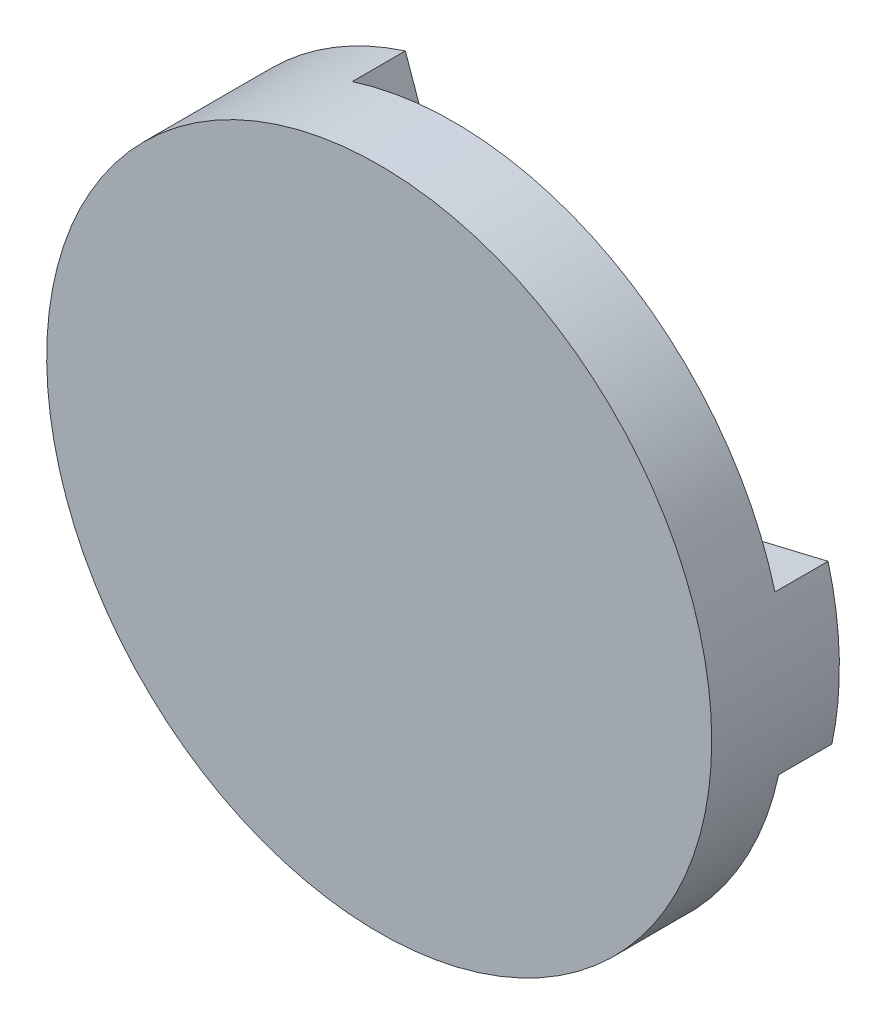
SolidWorks part; units mm, degrees
ref_plane "Front Plane" through (0, 0, 0) normal (0, 0, 1) x (1, 0, 0)
ref_plane "Top Plane" through (0, 0, 0) normal (0, 1, 0) x (1, 0, 0)
ref_plane "Right Plane" through (0, 0, 0) normal (1, 0, 0) x (0, 0, -1)
sketch "Sketch2" plane through (0, 0, 0) normal (0, 0, 1) x (1, 0, 0)
  line L0 (-57.2013, -53.6007) -> (-70.43, -69.0249) construction
  line L1 (-58.6979, -75.4263) -> (-52.8865, -55.955) construction
  line L2 (-37.8874, -46.8061) -> (-17.9153, -50.5504) construction
  line L3 (-18.2376, -37.1893) -> (-38.0059, -41.8922) construction
  line L4 (-53.4287, -33.477) -> (-60.1721, -14.3086) construction
  line L5 (-71.5819, -21.2682) -> (-57.625, -36.0366) construction
  line L6 (-57.2013, -53.6007) -> (-72.0836, -70.9529) construction
  line L7 (-59.4243, -77.8602) -> (-52.8865, -55.955) construction
  line L8 (-37.8874, -46.8061) -> (-15.4188, -51.0184) construction
  line L9 (-15.7666, -36.6015) -> (-38.0059, -41.8922) construction
  line L10 (-53.4287, -33.477) -> (-61.015, -11.9125) construction
  line L11 (-73.3265, -19.4221) -> (-57.625, -36.0366) construction
  line L26 (-39.1, -47.5962) -> (-14.634, -52.1829)
  line L27 (-15.0388, -35.4004) -> (-39.2552, -41.1615)
  line L28 (-52.1381, -34.1322) -> (-60.3989, -10.6506)
  line L29 (-74.7306, -19.3924) -> (-57.6331, -37.4839)
  line L30 (-58.7481, -79.091) -> (-51.629, -55.2384)
  line L31 (-57.2793, -52.1555) -> (-73.4845, -71.0503)
  arc A0 (-57.2013, -53.6007) -> (-52.8865, -55.955) centre (-49.5058, -44.6279) ccw construction
  arc A2 (-37.8874, -46.8061) -> (-38.0059, -41.8922) centre (-49.5058, -44.6279) ccw construction
  arc A4 (-53.4287, -33.477) -> (-57.625, -36.0366) centre (-49.5058, -44.6279) ccw construction
  arc A6 (-57.2013, -53.6007) -> (-52.8865, -55.955) centre (-49.5058, -44.6279) ccw construction
  arc A8 (-37.8874, -46.8061) -> (-38.0059, -41.8922) centre (-49.5058, -44.6279) ccw construction
  arc A10 (-53.4287, -33.477) -> (-57.625, -36.0366) centre (-49.5058, -44.6279) ccw construction
  arc A13 (-72.0836, -70.9529) -> (-59.4243, -77.8602) centre (-49.5058, -44.6279) ccw construction
  arc A15 (-15.4188, -51.0184) -> (-15.7666, -36.6015) centre (-49.5058, -44.6279) ccw construction
  arc A17 (-61.015, -11.9125) -> (-73.3265, -19.4221) centre (-49.5058, -44.6279) ccw construction
  arc A19 (-72.0836, -70.9529) -> (-59.4243, -77.8602) centre (-49.5058, -44.6279) ccw construction
  arc A21 (-15.4188, -51.0184) -> (-15.7666, -36.6015) centre (-49.5058, -44.6279) ccw construction
  arc A23 (-61.015, -11.9125) -> (-73.3265, -19.4221) centre (-49.5058, -44.6279) ccw construction
  arc A24 (-14.634, -52.1829) -> (-15.0388, -35.4004) centre (-49.5058, -44.6279) ccw
  arc A25 (-39.1, -47.5962) -> (-39.2552, -41.1615) centre (-49.5058, -44.6279) ccw
  arc A26 (-60.3989, -10.6506) -> (-74.7306, -19.3924) centre (-49.5058, -44.6279) ccw
  arc A27 (-52.1381, -34.1322) -> (-57.6331, -37.4839) centre (-49.5058, -44.6279) ccw
  arc A28 (-57.2793, -52.1555) -> (-51.629, -55.2384) centre (-49.5058, -44.6279) ccw
  arc A29 (-73.4845, -71.0503) -> (-58.7481, -79.091) centre (-49.5058, -44.6279) ccw
  dimension "D1" = 1
  dimension "D2" = 1
  dimension "D3" = 1
extrude "Boss-Extrude1" add sketch "Sketch2" along normal blind 12.7 contours L7 A6 L6 A19 | L10 A23 L11 A10 | L8 A21 L9 A8 | L26 A24 L27 A25 | L30 A28 L31 A29 | L28 A26 L29 A27
sketch "Sketch3" plane through (0, 0, 12.7) normal (0, 0, 1) x (1, 0, 0)
  circle A0 centre (-49.5058, -44.6279) radius 35.6808
  arc A2 (-60.3989, -10.6506) -> (-74.7306, -19.3924) centre (-49.5058, -44.6279) ccw construction
extrude "Boss-Extrude2" add sketch "Sketch3" along normal blind 1
sketch "Sketch4" plane through (0, 0, 0) normal (0, 0, -1) x (-1, 0, 0)
  line L6 (72.7863, -71.0042) -> (57.2482, -52.8873)
  line L7 (52.2612, -55.6083) -> (59.0872, -78.4789)
  line L8 (72.7863, -71.0042) -> (57.2482, -52.8873)
  line L9 (52.2612, -55.6083) -> (59.0872, -78.4789)
  line L12 (38.6188, -41.524) -> (15.3993, -36.0002)
  line L13 (15.023, -51.6013) -> (38.4818, -47.2034)
  line L14 (38.6188, -41.524) -> (15.3993, -36.0002)
  line L15 (15.023, -51.6013) -> (38.4818, -47.2034)
  line L18 (57.6374, -36.7515) -> (74.0309, -19.4048)
  line L19 (60.7081, -11.2783) -> (52.7874, -33.7932)
  line L20 (57.6374, -36.7515) -> (74.0309, -19.4048)
  line L21 (60.7081, -11.2783) -> (52.7874, -33.7932)
  arc A6 (59.0872, -78.4789) -> (72.7863, -71.0042) centre (49.5058, -44.6279) ccw
  arc A7 (52.2612, -55.6083) -> (57.2482, -52.8873) centre (49.5058, -44.6279) ccw
  arc A8 (59.0872, -78.4789) -> (72.7863, -71.0042) centre (49.5058, -44.6279) ccw
  arc A9 (52.2612, -55.6083) -> (57.2482, -52.8873) centre (49.5058, -44.6279) ccw
  arc A12 (38.6188, -41.524) -> (38.4818, -47.2034) centre (49.5058, -44.6279) ccw
  arc A13 (15.3993, -36.0002) -> (15.023, -51.6013) centre (49.5058, -44.6279) ccw
  arc A14 (38.6188, -41.524) -> (38.4818, -47.2034) centre (49.5058, -44.6279) ccw
  arc A15 (15.3993, -36.0002) -> (15.023, -51.6013) centre (49.5058, -44.6279) ccw
  arc A18 (57.6374, -36.7515) -> (52.7874, -33.7932) centre (49.5058, -44.6279) ccw
  arc A19 (74.0309, -19.4048) -> (60.7081, -11.2783) centre (49.5058, -44.6279) ccw
  arc A20 (57.6374, -36.7515) -> (52.7874, -33.7932) centre (49.5058, -44.6279) ccw
  arc A21 (74.0309, -19.4048) -> (60.7081, -11.2783) centre (49.5058, -44.6279) ccw
  dimension "D1" = 0.5
  dimension "D2" = 0.5
  dimension "D3" = 0.5
extrude "Cut-Extrude1" cut sketch "Sketch4" against normal blind 3
sketch "Sketch5" plane through (0, 0, 12.7) normal (0, 0, -1) x (-1, 0, 0)
  line L12 (73.4845, -71.0503) -> (73.1485, -70.6801)
  line L13 (74.7306, -19.3924) -> (74.3771, -19.746)
  line L14 (14.634, -52.1829) -> (15.1226, -52.0771)
  line L15 (58.7481, -79.091) -> (58.6185, -78.6081)
  line L16 (15.5218, -35.5297) -> (15.0388, -35.4004)
  line L17 (60.2462, -11.1267) -> (60.3989, -10.6506)
  arc A8 (60.3989, -10.6506) -> (15.0388, -35.4004) centre (49.5058, -44.6279) ccw
  arc A10 (14.634, -52.1829) -> (58.7481, -79.091) centre (49.5058, -44.6279) ccw
  arc A14 (73.4845, -71.0503) -> (74.7306, -19.3924) centre (49.5058, -44.6279) ccw
  arc A15 (73.1485, -70.6801) -> (74.3771, -19.746) centre (49.5058, -44.6279) ccw
  arc A16 (15.1226, -52.0771) -> (58.6185, -78.6081) centre (49.5058, -44.6279) ccw
  arc A19 (60.2462, -11.1267) -> (15.5218, -35.5297) centre (49.5058, -44.6279) ccw
  arc A20 (60.2462, -11.1267) -> (15.5218, -35.5297) centre (49.5058, -44.6279) ccw
  dimension "D2" = 0.5
  dimension "D3" = 0.5
  dimension "D4" = 0.5
extrude "Boss-Extrude3" add sketch "Sketch5" along normal blind 7
